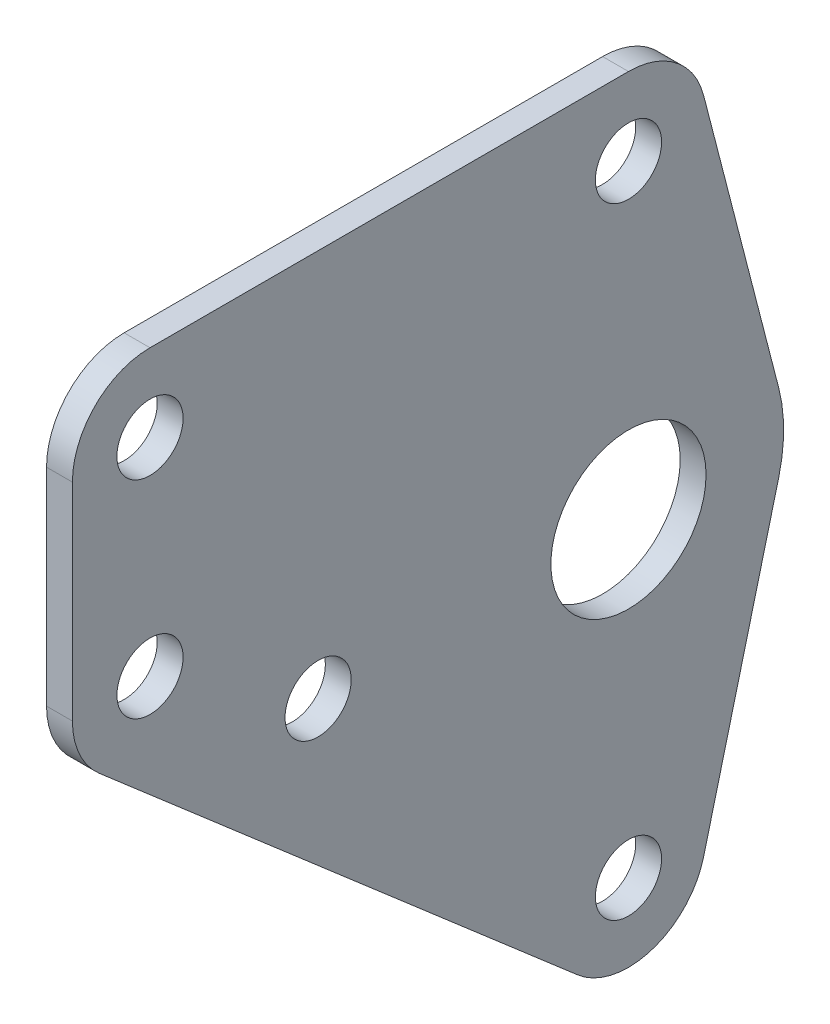
SolidWorks part; units mm, degrees
ref_plane "Front Plane" through (0, 0, 0) normal (0, 0, 1) x (1, 0, 0)
ref_plane "Top Plane" through (0, 0, 0) normal (0, 1, 0) x (1, 0, 0)
ref_plane "Right Plane" through (0, 0, 0) normal (1, 0, 0) x (0, 0, -1)
sketch "Sketch1" plane through (0, 0, 0) normal (1, 0, 0) x (0, 0, -1)
  line L6 (-19.05, 0) -> (0, 0) construction
  line L7 (0, 0) -> (0, 19.05) construction
  line L8 (0, 0) -> (0, -19.05) construction
  line L9 (0, 19.05) -> (-19.05, 0) construction
  line L10 (-19.05, 0) -> (0, -19.05) construction
  line L11 (-3.3676, 22.4176) -> (-22.4176, 3.3676)
  line L12 (-22.4176, -3.3676) -> (-3.3676, -22.4176)
  line L15 (-25.7852, 0) -> (4.7625, -30.5477) construction
  line L16 (4.7625, 0) -> (4.7625, -30.5477) construction
  line L17 (4.7625, 30.5477) -> (-25.7852, 0) construction
  line L18 (4.7625, 0) -> (4.7625, 30.5477) construction
  line L19 (4.6113, 20.2406) -> (9.2225, 2.3813)
  line L20 (9.2225, -2.3813) -> (4.6113, -20.2406)
  circle A10 centre (0, 0) radius 4.7625
  circle A11 centre (0, 19.05) radius 2.032
  circle A12 centre (-19.05, 0) radius 2.032
  circle A13 centre (0, -19.05) radius 2.032
  arc A16 (-22.4176, 3.3676) -> (-22.4176, -3.3676) centre (-19.05, 0) ccw
  arc A17 (9.2225, 2.3813) -> (9.2225, -2.3813) centre (0, 0) cw
  arc A18 (-3.3676, 22.4176) -> (4.6113, 20.2406) centre (0, 19.05) cw
  arc A19 (4.6113, -20.2406) -> (-3.3676, -22.4176) centre (0, -19.05) cw
  dimension "D1" = 9.525
  dimension "D2" = 19.05
  dimension "D5" = 9.525
  dimension "D3" = 4.064
  dimension "D4" = 4.7625
extrude "Boss-Extrude1" add sketch "Sketch1" along normal blind 1.5875
sketch "Sketch2" plane through (1.5875, 0, 0) normal (1, 0, 0) x (0, 0, -1)
  line L0 (-3.1154, -22.6522) -> (-32.4841, 2.7478)
  line L1 (-34.1313, 6.35) -> (-34.1313, 19.05)
  line L2 (-29.3687, 23.8125) -> (0, 23.8125)
  line L3 (-3.3676, 22.4176) -> (-22.4176, 3.3676) construction
  line L4 (-22.4176, -3.3676) -> (-3.3676, -22.4176) construction
  line L5 (-3.3676, 22.4176) -> (-22.4176, 3.3676)
  line L6 (-22.4176, -3.3676) -> (-3.3676, -22.4176)
  circle A0 centre (-29.3687, 6.35) radius 2.032
  circle A1 centre (-29.3687, 19.05) radius 2.032
  circle A2 centre (0, 19.05) radius 2.032 construction
  circle A3 centre (-19.05, 0) radius 2.032 construction
  arc A4 (-34.1313, 6.35) -> (-32.4841, 2.7478) centre (-29.3687, 6.35) ccw
  arc A5 (-29.3687, 23.8125) -> (-34.1313, 19.05) centre (-29.3687, 19.05) ccw
  arc A6 (4.6113, 20.2406) -> (-3.3676, 22.4176) centre (0, 19.05) ccw construction
  arc A7 (-3.3676, -22.4176) -> (4.6113, -20.2406) centre (0, -19.05) ccw construction
  arc A8 (-22.4176, 3.3676) -> (-22.4176, -3.3676) centre (-19.05, 0) ccw construction
  arc A9 (-3.3676, -22.4176) -> (-3.1154, -22.6522) centre (0, -19.05) ccw
  arc A10 (0, 23.8125) -> (-3.3676, 22.4176) centre (0, 19.05) ccw
  arc A11 (-22.4176, 3.3676) -> (-22.4176, -3.3676) centre (-19.05, 0) ccw
  point P4 (0, 0)
  point P22 (-0.9392, 23.719)
  dimension "D1" = 12.7
  dimension "D2" = 6.35
  dimension "D3" = 10.3187
extrude "Boss-Extrude2" add sketch "Sketch2" against normal up to surface (1.5875 mm away) up to face at (0, 0, 17.018)
